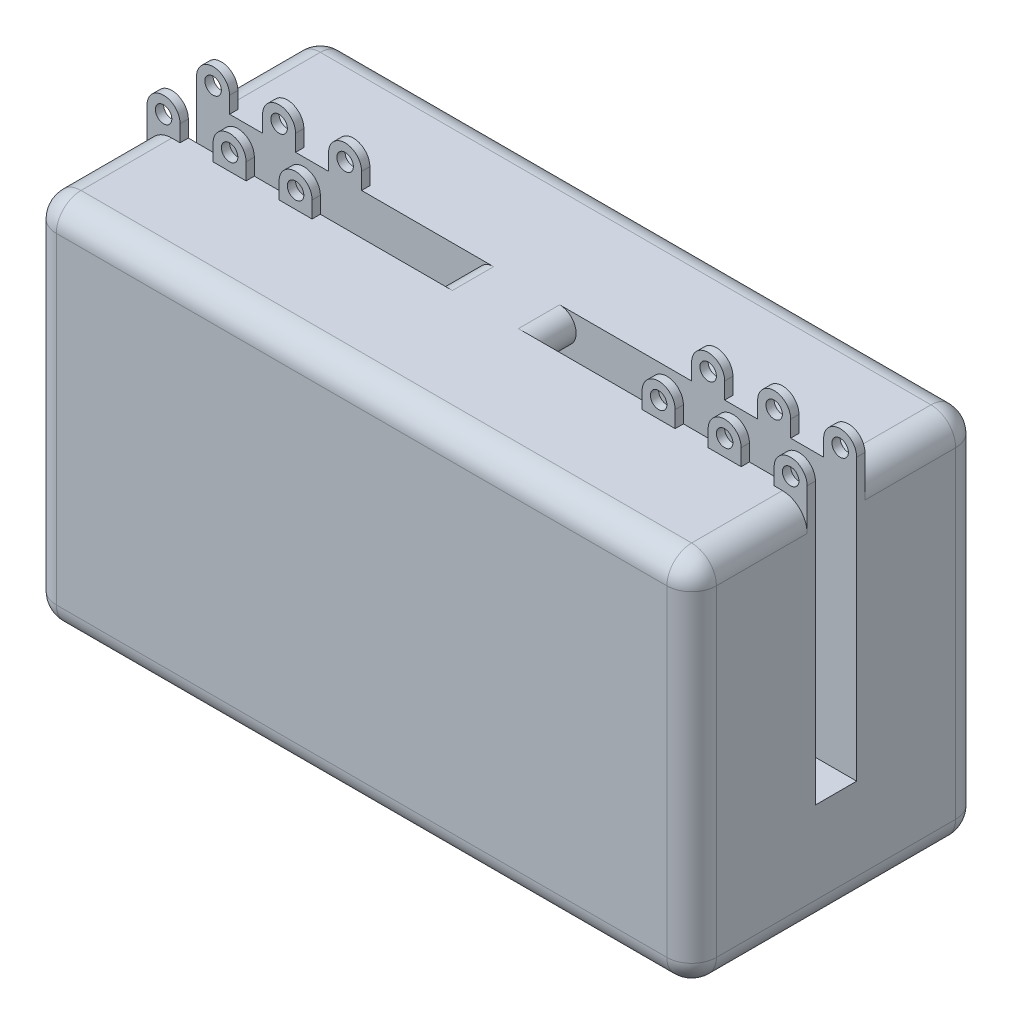
SolidWorks part; units mm, degrees
ref_plane "前视基准面" through (0, 0, 0) normal (0, 0, 1) x (1, 0, 0)
ref_plane "上视基准面" through (0, 0, 0) normal (0, 1, 0) x (1, 0, 0)
ref_plane "右视基准面" through (0, 0, 0) normal (1, 0, 0) x (0, 0, -1)
other "Configuration Table"
sketch "草图1" plane through (0, 0, 0) normal (0, 0, 1) x (1, 0, 0)
  line L1 (-400, 225) -> (400, 225)
  line L2 (-400, 225) -> (-400, -225)
  line L3 (-400, -225) -> (400, -225)
  line L4 (400, 225) -> (400, -225)
  line L5 (-400, 225) -> (400, -225) construction
  line L6 (-400, -225) -> (400, 225) construction
  point P0 (0, 0)
  dimension "D1" = 800
  dimension "D2" = 450
extrude "凸台-拉伸1" add sketch "草图1" along normal blind 150
sketch "草图2" plane through (0, 0, 0) normal (0, 0, -1) x (-1, 0, 0)
  line L0 (-400, 225) -> (400, 225) construction
  line L1 (400, 225) -> (400, -225) construction
  line L2 (400, 245) -> (400, 225)
  line L3 (400, 225) -> (360, 225)
  line L4 (360, 225) -> (360, 245)
  line L8 (240, 245) -> (240, 225)
  line L9 (240, 225) -> (200, 225)
  line L10 (200, 225) -> (200, 245)
  line L14 (-200, 245) -> (-200, 225)
  line L15 (-200, 225) -> (-240, 225)
  line L16 (-240, 225) -> (-240, 245)
  line L17 (-360, 245) -> (-360, 225)
  line L18 (-360, 225) -> (-400, 225)
  line L19 (-400, 225) -> (-400, 245)
  line L20 (-400, -225) -> (-400, 225) construction
  line L21 (-280, 245) -> (-280, 225)
  line L22 (-280, 225) -> (-320, 225)
  line L23 (-320, 225) -> (-320, 245)
  line L24 (320, 245) -> (320, 225)
  line L25 (320, 225) -> (280, 225)
  line L26 (280, 225) -> (280, 245)
  circle A0 centre (380, 245) radius 10
  arc A1 (400, 245) -> (360, 245) centre (380, 245) ccw
  circle A4 centre (220, 245) radius 10
  arc A5 (240, 245) -> (200, 245) centre (220, 245) ccw
  circle A8 centre (-220, 245) radius 10
  arc A9 (-200, 245) -> (-240, 245) centre (-220, 245) ccw
  circle A10 centre (-380, 245) radius 10
  arc A11 (-360, 245) -> (-400, 245) centre (-380, 245) ccw
  circle A12 centre (-300, 245) radius 10
  arc A13 (-280, 245) -> (-320, 245) centre (-300, 245) ccw
  circle A14 centre (300, 245) radius 10
  arc A15 (320, 245) -> (280, 245) centre (300, 245) ccw
  dimension "D1" = 20
  dimension "D5" = 20
  dimension "D6" = 20
  dimension "D4" = 20
  dimension "D9" = 20
  dimension "D12" = 20
  dimension "D13" = 20
  dimension "D18" = 20
  dimension "D19" = 20
  dimension "D23" = 20
  dimension "D24" = 20
  dimension "D2" = 20
  dimension "D3" = 160
  dimension "D7" = 20
  dimension "D8" = 40
  dimension "D10" = 20
  dimension "D11" = 40
  dimension "D14" = 20
  dimension "D15" = 40
  dimension "D16" = 160
  dimension "D17" = 20
  dimension "D20" = 20
  dimension "D21" = 40
  dimension "D22" = 80
  dimension "D25" = 20
  dimension "D26" = 40
  dimension "D27" = 80
extrude "凸台-拉伸2" add sketch "草图2" against normal blind 10
sketch "草图3" plane through (0, 0, 0) normal (0, 0, -1) x (-1, 0, 0)
  line L0 (-40, 205) -> (40, 205) construction
  line L1 (-40, 225) -> (40, 225)
  line L2 (-40, 185) -> (40, 185)
  line L3 (-200, 225) -> (200, 225) construction
  line L4 (400, 245) -> (400, -225) construction
  line L8 (-400, -225) -> (400, -225)
  line L9 (-400, -225) -> (-400, -95)
  line L10 (-400, -95) -> (400, -95)
  line L11 (400, -225) -> (400, -95)
  arc A0 (-40, 225) -> (-40, 185) centre (-40, 205) ccw
  arc A1 (40, 185) -> (40, 225) centre (40, 205) ccw
  point P2 (0, 205)
  dimension "D2" = 20
  dimension "D4" = 130
  dimension "D1" = 80
  dimension "D3" = 20
extrude "凸台-拉伸3" add sketch "草图3" along normal blind 50
sketch "草图4" plane through (0, 0, -50) normal (0, 0, -1) x (-1, 0, 0)
  line L1 (-400, -225) -> (400, -225)
  line L2 (-400, -225) -> (-400, 225)
  line L3 (-400, 225) -> (400, 225)
  line L4 (400, -225) -> (400, 225)
extrude "凸台-拉伸4" add sketch "草图4" along normal blind 150 contours L4 L3 L2 L1
sketch "草图5" plane through (0, 0, -50) normal (0, 0, 1) x (1, 0, 0)
  line L0 (400, 245) -> (400, 225)
  line L1 (400, 225) -> (360, 225)
  line L2 (360, 225) -> (360, 245)
  line L3 (240, 245) -> (240, 225)
  line L4 (240, 225) -> (200, 225)
  line L5 (200, 225) -> (200, 245)
  line L6 (-200, 245) -> (-200, 225)
  line L7 (-200, 225) -> (-240, 225)
  line L8 (-240, 225) -> (-240, 245)
  line L9 (-360, 245) -> (-360, 225)
  line L10 (-360, 225) -> (-400, 225)
  line L11 (-400, 225) -> (-400, 245)
  line L12 (-280, 245) -> (-280, 225)
  line L13 (-280, 225) -> (-320, 225)
  line L14 (-320, 225) -> (-320, 245)
  line L15 (320, 245) -> (320, 225)
  line L16 (320, 225) -> (280, 225)
  line L17 (280, 225) -> (280, 245)
  circle A0 centre (380, 245) radius 10
  arc A1 (400, 245) -> (360, 245) centre (380, 245) ccw
  circle A2 centre (220, 245) radius 10
  arc A3 (240, 245) -> (200, 245) centre (220, 245) ccw
  circle A4 centre (-220, 245) radius 10
  arc A5 (-200, 245) -> (-240, 245) centre (-220, 245) ccw
  circle A6 centre (-380, 245) radius 10
  arc A7 (-360, 245) -> (-400, 245) centre (-380, 245) ccw
  circle A8 centre (-300, 245) radius 10
  arc A9 (-280, 245) -> (-320, 245) centre (-300, 245) ccw
  circle A10 centre (300, 245) radius 10
  arc A11 (320, 245) -> (280, 245) centre (300, 245) ccw
  dimension "D2" = 20
  dimension "D3" = 20
  dimension "D6" = 20
  dimension "D7" = 20
  dimension "D10" = 20
  dimension "D11" = 20
  dimension "D15" = 20
  dimension "D16" = 20
  dimension "D20" = 20
  dimension "D21" = 20
  dimension "D1" = 160
  dimension "D4" = 20
  dimension "D5" = 40
  dimension "D8" = 20
  dimension "D9" = 40
  dimension "D12" = 20
  dimension "D13" = 40
  dimension "D14" = 160
  dimension "D17" = 20
  dimension "D18" = 40
  dimension "D19" = 80
  dimension "D22" = 20
  dimension "D23" = 40
  dimension "D24" = 80
extrude "凸台-拉伸5" add sketch "草图5" against normal blind 10
fillet "圆角1" radius 30 14 edges at (-400, 225, 80) (-400, 225, -130) (0, -225, -200) (-400, -225, -25) (-400, 0, -200) (-400, 0, 150) (0, -225, 150) (400, -225, -25) (0, 225, -200) (400, 0, -200) (0, 225, 150) (400, 0, 150) (400, 225, -130) (400, 225, 80)
